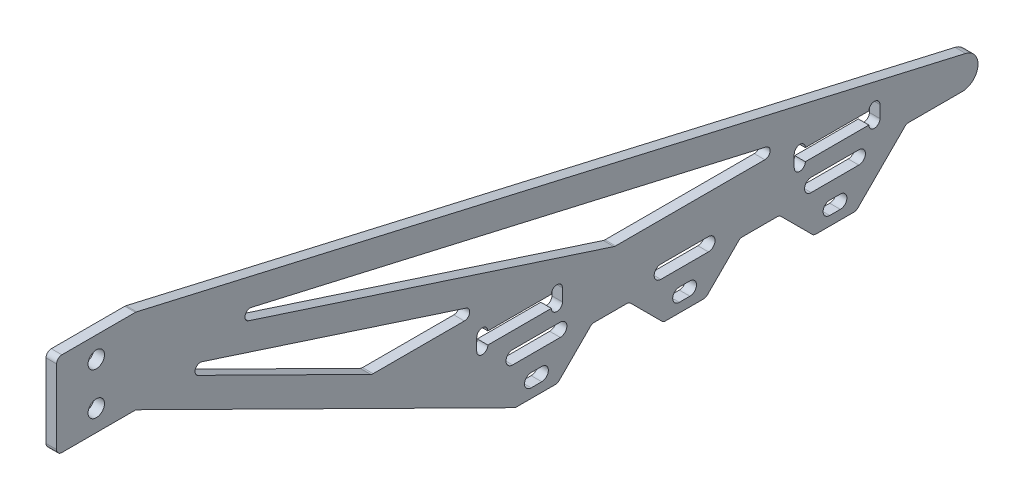
SolidWorks part; units mm, degrees
material "Thornel Mat VMA"
ref_plane "前视基准面" through (0, 0, 0) normal (0, 0, 1) x (1, 0, 0)
ref_plane "上视基准面" through (0, 0, 0) normal (0, 1, 0) x (1, 0, 0)
ref_plane "右视基准面" through (0, 0, 0) normal (1, 0, 0) x (0, 0, -1)
sketch "草图1" plane through (0, 0, 0) normal (1, 0, 0) x (0, 0, -1)
  line L0 (-7.5, 12) -> (-7.5, -4)
  line L2 (60, -30) -> (153.1, -30) construction
  line L3 (153.1, -30) -> (153.1, -21.5) construction
  line L5 (75.2504, -25.5) -> (148.0856, -25.5) construction
  line L6 (-7.5, 12) -> (7.5, 12)
  line L7 (88.1, -26.65) -> (71.9, -26.65)
  line L8 (88.1, -26.65) -> (88.1, -24.35)
  line L9 (88.1, -24.35) -> (71.9, -24.35)
  line L10 (71.9, -26.65) -> (71.9, -24.35)
  line L11 (88.1, -26.65) -> (71.9, -24.35) construction
  line L12 (88.1, -24.35) -> (71.9, -26.65) construction
  line L13 (148.1, -26.65) -> (131.9, -26.65)
  line L14 (148.1, -26.65) -> (148.1, -24.35)
  line L15 (148.1, -24.35) -> (131.9, -24.35)
  line L16 (131.9, -26.65) -> (131.9, -24.35)
  line L17 (148.1, -26.65) -> (131.9, -24.35) construction
  line L18 (148.1, -24.35) -> (131.9, -26.65) construction
  line L19 (7.5, 12) -> (153.1, -21.5)
  line L20 (-7.5, -4) -> (7.5, -4)
  line L21 (7.5, -4) -> (60, -30)
  line L22 (7, 1.8272) -> (52.0837, -20.5)
  line L23 (52.0837, -20.5) -> (75.8909, -20.5)
  line L24 (75.8909, -20.5) -> (7, 1.8272)
  line L25 (7, 6.9844) -> (97.9746, -22.5)
  line L26 (97.9746, -22.5) -> (135.1471, -22.5)
  line L27 (135.1471, -22.5) -> (7, 6.9844)
  line L33 (60, -30) -> (79.1827, -39.5)
  line L34 (79.1827, -39.5) -> (87.1827, -39.5)
  line L35 (87.1827, -39.5) -> (96.6827, -30) construction
  line L36 (97.6827, -30) -> (107.1827, -39.5) construction
  line L37 (107.1827, -39.5) -> (115.1827, -39.5)
  line L38 (115.1827, -39.5) -> (124.6827, -30) construction
  line L39 (126.1, -30) -> (135.6, -39.5) construction
  line L40 (135.6, -39.5) -> (143.6, -39.5)
  line L41 (143.6, -39.5) -> (153.1, -30)
  line L42 (111.1827, -39.5) -> (111.1827, -31.2199) construction
  line L43 (83.1827, -39.5) -> (83.1827, -31.2199) construction
  line L44 (96.6827, -30) -> (97.6827, -30) construction
  line L45 (124.6827, -30) -> (126.1, -30) construction
  line L46 (153.1, -30) -> (190.0433, -30)
  line L47 (190.0433, -30) -> (153.1, -21.5)
  line L48 (78.6827, -31) -> (87.6827, -31) construction
  line L49 (78.6827, -29.75) -> (87.6827, -29.75)
  line L50 (78.6827, -32.25) -> (87.6827, -32.25)
  line L51 (106.6827, -31) -> (115.6827, -31) construction
  line L52 (106.6827, -29.75) -> (115.6827, -29.75)
  line L53 (106.6827, -32.25) -> (115.6827, -32.25)
  line L54 (135.1, -31) -> (144.1, -31) construction
  line L55 (135.1, -29.75) -> (144.1, -29.75)
  line L56 (135.1, -32.25) -> (144.1, -32.25)
  line L57 (139.6, -39.5) -> (139.6, -41.3743) construction
  line L58 (82.1827, -36.5) -> (84.1827, -36.5) construction
  line L59 (82.1827, -35.25) -> (84.1827, -35.25)
  line L60 (82.1827, -37.75) -> (84.1827, -37.75)
  line L61 (110.1827, -36.5) -> (112.1827, -36.5) construction
  line L62 (110.1827, -35.25) -> (112.1827, -35.25)
  line L63 (110.1827, -37.75) -> (112.1827, -37.75)
  line L64 (138.6, -36.5) -> (140.6, -36.5) construction
  line L65 (138.6, -35.25) -> (140.6, -35.25)
  line L66 (138.6, -37.75) -> (140.6, -37.75)
  line L67 (93.6827, -33) -> (100.6827, -33)
  line L68 (121.6827, -33) -> (129.1, -33)
  line L69 (87.1827, -39.5) -> (93.6827, -33)
  line L70 (100.6827, -33) -> (107.1827, -39.5)
  line L71 (115.1827, -39.5) -> (121.6827, -33)
  line L72 (129.1, -33) -> (135.6, -39.5)
  circle A0 centre (0, 0) radius 1.55
  circle A1 centre (0, 8) radius 1.55
  circle A2 centre (132.95, -24.35) radius 1.05
  circle A3 centre (147.05, -24.35) radius 1.05
  circle A4 centre (132.95, -26.65) radius 1.05
  circle A5 centre (147.05, -26.65) radius 1.05
  circle A6 centre (72.95, -24.35) radius 1.05
  circle A7 centre (87.05, -24.35) radius 1.05
  circle A8 centre (87.05, -26.65) radius 1.05
  circle A9 centre (72.95, -26.65) radius 1.05
  arc A10 (78.6827, -29.75) -> (78.6827, -32.25) centre (78.6827, -31) ccw
  arc A11 (87.6827, -32.25) -> (87.6827, -29.75) centre (87.6827, -31) ccw
  arc A12 (106.6827, -29.75) -> (106.6827, -32.25) centre (106.6827, -31) ccw
  arc A13 (115.6827, -32.25) -> (115.6827, -29.75) centre (115.6827, -31) ccw
  arc A14 (135.1, -29.75) -> (135.1, -32.25) centre (135.1, -31) ccw
  arc A15 (144.1, -32.25) -> (144.1, -29.75) centre (144.1, -31) ccw
  arc A16 (82.1827, -35.25) -> (82.1827, -37.75) centre (82.1827, -36.5) ccw
  arc A17 (84.1827, -37.75) -> (84.1827, -35.25) centre (84.1827, -36.5) ccw
  arc A18 (110.1827, -35.25) -> (110.1827, -37.75) centre (110.1827, -36.5) ccw
  arc A19 (112.1827, -37.75) -> (112.1827, -35.25) centre (112.1827, -36.5) ccw
  arc A20 (138.6, -35.25) -> (138.6, -37.75) centre (138.6, -36.5) ccw
  arc A21 (140.6, -37.75) -> (140.6, -35.25) centre (140.6, -36.5) ccw
  point P10 (140, -25.5)
  point P13 (80, -25.5)
  point P63 (83.1827, -31)
  point P68 (111.1827, -31)
  point P75 (139.6, -31)
  point P86 (83.1827, -36.5)
  point P93 (111.1827, -36.5)
  point P98 (139.6, -36.5)
  dimension "D2" = 3.1
  dimension "D8" = 2.1
  dimension "D26" = 1.25
  dimension "D30" = 1.25
  dimension "D1" = 8
  dimension "D3" = 7.5
  dimension "D4" = 60
  dimension "D5" = 80
  dimension "D6" = 2.3
  dimension "D7" = 16.2
  dimension "D9" = 25.5
  dimension "D10" = 4.5
  dimension "D11" = 20
  dimension "D12" = 5
  dimension "D13" = 4
  dimension "D14" = 4
  dimension "D15" = 15
  dimension "D16" = 4
  dimension "D17" = 7
  dimension "D18" = 5
  dimension "D19" = 5
  dimension "D20" = 5
  dimension "D21" = 3
  dimension "D22" = 45
  dimension "D23" = 3
  dimension "D24" = 8
  dimension "D25" = 28
  dimension "D27" = 9
  dimension "D28" = 5.5
  dimension "D29" = 3
  dimension "D31" = 2
  dimension "D32" = 3
  dimension "D33" = 9.5
extrude "凸台-拉伸1" add sketch "草图1" along normal blind 2 contours L20 L21 L2 L3 L19 L6 L0 A9 L10 A6 L9 A7 L8 A8 L7 A5 L13 A4 L16 A2 L15 A3 L14 A1 A0 L27 L26 L25 L24 L23 L22
fillet "圆角1" radius 1 21 edges at (1, -22.5, -97.9746) (1, -22.5, -135.1471) (1, -20.5, -75.8909) (1, -4, -7.5) (1, -20.5, -52.0837) (1, 1.8272, -7) (1, 6.9844, -7) (1, -30, -153.1) (1, -39.5, -143.6) (1, -39.5, -79.1827) (1, 12, -7.5) (1, 12, 7.5) (1, -4, 7.5) (1, -33, -121.6827) (1, -39.5, -107.1827) (1, -33, -100.6827) (1, -33, -93.6827) (1, -39.5, -87.1827) (1, -39.5, -135.6) (1, -33, -129.1) (1, -39.5, -115.1827)
fillet "圆角2" radius 3 1 edges at (1, -30, -190.0433)
